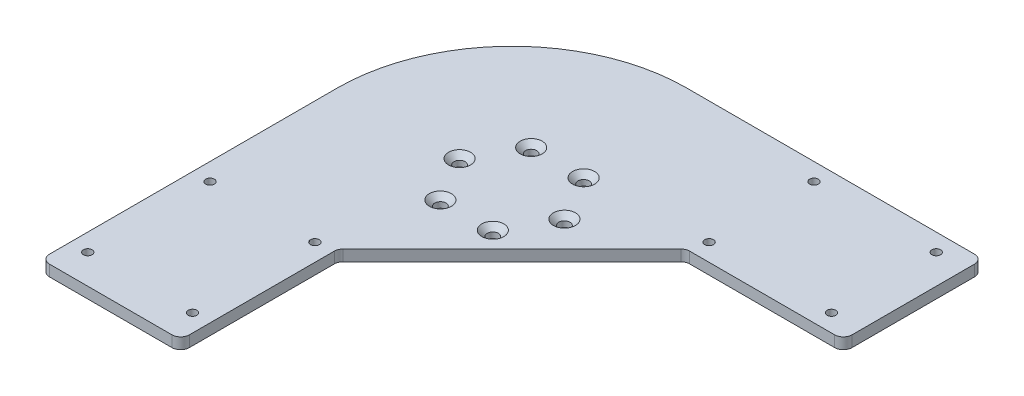
SolidWorks part; units mm, degrees
material "6061 Alloy"
ref_plane "Front Plane" through (0, 0, 0) normal (0, 0, 1) x (1, 0, 0)
ref_plane "Top Plane" through (0, 0, 0) normal (0, 1, 0) x (1, 0, 0)
ref_plane "Right Plane" through (0, 0, 0) normal (1, 0, 0) x (0, 0, -1)
sketch "Sketch1" plane through (0, 0, 0) normal (0, 1, 0) x (1, 0, 0)
  line L0 (0, 100) -> (169.625, 100)
  line L1 (169.625, 100) -> (169.625, 20)
  line L2 (169.625, 20) -> (79.625, 20)
  line L5 (-20, -79.625) -> (-20, -169.625)
  line L6 (-20, -169.625) -> (-100, -169.625)
  line L7 (-100, -169.625) -> (-100, 0)
  line L8 (-70.7107, 70.7107) -> (0, 0) construction
  line L9 (82.8, 90) -> (152.8, 90) construction
  line L10 (82.8, 90) -> (82.8, 30) construction
  line L11 (82.8, 30) -> (152.8, 30) construction
  line L12 (152.8, 90) -> (152.8, 30) construction
  line L13 (-20, -79.625) -> (79.625, 20)
  circle A0 centre (82.8, 90) radius 3 construction
  circle A1 centre (152.8, 90) radius 3 construction
  circle A2 centre (152.8, 30) radius 3 construction
  circle A3 centre (82.8, 30) radius 3 construction
  circle A4 centre (0, 0) radius 30 construction
  circle A5 centre (-30, 0) radius 3 construction
  circle A6 centre (-15, 25.9808) radius 3 construction
  circle A7 centre (15, 25.9808) radius 3 construction
  circle A8 centre (30, 0) radius 3 construction
  circle A9 centre (15, -25.9808) radius 3 construction
  circle A10 centre (-15, -25.9808) radius 3 construction
  circle A11 centre (-90, -152.8) radius 3 construction
  circle A12 centre (-30, -152.8) radius 3 construction
  circle A13 centre (-30, -82.8) radius 3 construction
  circle A14 centre (-90, -82.8) radius 3 construction
  arc A15 (0, 100) -> (-100, 0) centre (0, 0) ccw
  point P13 (152.8, 60)
  point P14 (169.625, 60)
  point P37 (0, 0)
  dimension "D1" = 6
  dimension "D6" = 60
  dimension "D7" = 6
  dimension "D9" = 30
  dimension "D10" = 82.8
  dimension "D11" = 90
  dimension "D2" = 70
  dimension "D3" = 60
  dimension "D4" = 80
  dimension "D5" = 16.825
  dimension "D8" = 6
extrude "Boss-Extrude1" add sketch "Sketch1" against normal blind 6.35
fillet "Fillet1" radius 5 6 edges at (169.625, -3.175, -100) (169.625, -3.175, -20) (79.625, -3.175, -20) (-20, -3.175, 79.625) (-100, -3.175, 169.625) (-20, -3.175, 169.625)
hole_wizard "Tap Drill for M6x1.0 Tap1" positions "3DSketch1" profile "Sketch2" hole size "M6x1.0" standard "ANSI Metric" end condition up to next
sketch3d "3DSketch1"
  point P0 (82.8, 0, -90)
  point P5 (152.8, 0, -90)
  point P7 (152.8, 0, -30)
  point P19 (-90, 0, 82.8)
  point P21 (-30, 0, 82.8)
  point P23 (-30, 0, 152.8)
  point P25 (-90, 0, 152.8)
  point P52 (82.8, 0, -30)
sketch "Sketch2" plane through (82.8, 0, -90) normal (1, 0, 0) x (0, 0, 1)
  line L0 (0, 0) -> (0, 6.35)
  line L1 (0, 6.35) -> (2.5, 6.35)
  line L2 (2.5, 6.35) -> (2.5, 0)
  line L5 (2.5, 0) -> (0, 0)
  line L11 (0, -6.35) -> (0, 107.95) construction
  dimension "Thru Hole Dia." = 5
  dimension "Thru Hole Depth" = 6.35
hole_wizard "CSK for M6 Flat Head Machine Screw1" positions "3DSketch2" profile "Sketch3" countersink size "M6" standard "ANSI Metric" end condition up to next
sketch3d "3DSketch2"
  point P0 (15, 0, -25.9808)
  point P2 (30, 0, 0)
  point P4 (15, 0, 25.9808)
  point P6 (-15, 0, 25.9808)
  point P8 (-30, 0, 0)
  point P10 (-15, 0, -25.9808)
sketch "Sketch3" plane through (15, 0, -25.9808) normal (1, 0, 0) x (0, 0, 1)
  line L0 (0, 0) -> (0, 6.35)
  line L1 (0, 6.35) -> (3.2, 6.35)
  line L2 (3.2, 6.35) -> (3.2, 3.1)
  line L3 (3.2, 3.1) -> (6.3, 0)
  line L5 (6.3, 0) -> (0, 0)
  line L6 (-3.2, 3.1) -> (-6.3, 0) construction
  line L11 (0, -6.35) -> (0, 107.95) construction
  dimension "Thru Hole Dia." = 6.4
  dimension "Thru Hole Depth" = 6.35
  dimension "Near C'Sink Dia." = 12.6
  dimension "Near C'Sink Angle" = 90
